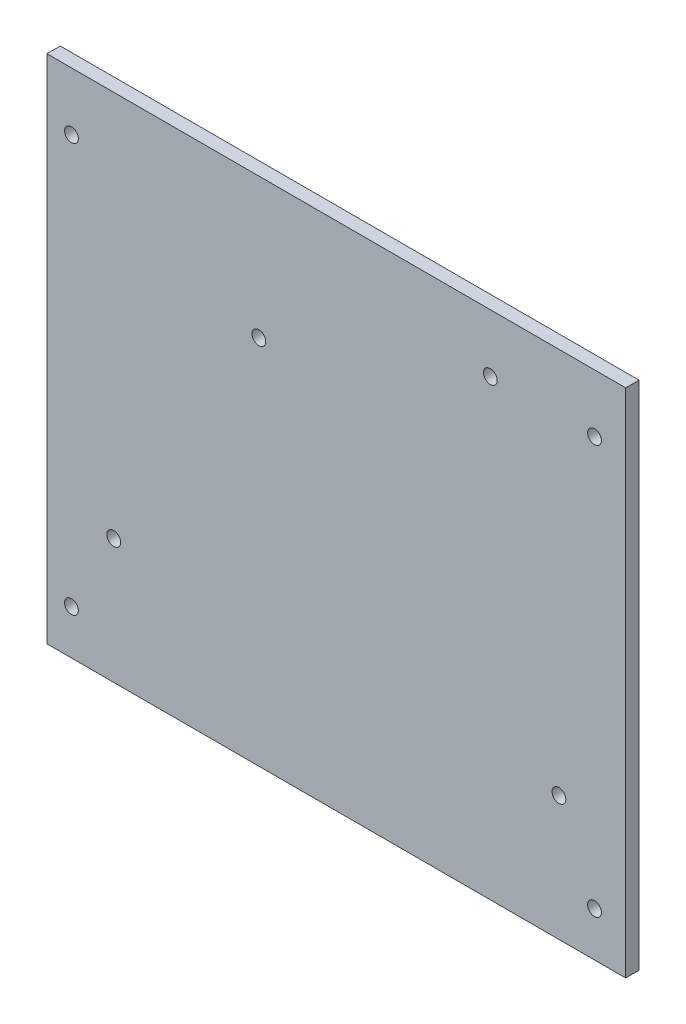
SolidWorks part; units mm, degrees
ref_plane "Front" through (0, 0, 0) normal (0, 0, 1) x (1, 0, 0)
ref_plane "Top" through (0, 0, 0) normal (0, 1, 0) x (1, 0, 0)
ref_plane "Right" through (0, 0, 0) normal (1, 0, 0) x (0, 0, -1)
sketch "Sketch1" plane through (0, 0, 0) normal (0, 0, 1) x (1, 0, 0)
  line L0 (65, 0) -> (0, 0) construction
  line L1 (-65, -57.4) -> (65, -57.4)
  line L2 (-65, -57.4) -> (-65, 57.4)
  line L3 (-65, 57.4) -> (65, 57.4)
  line L4 (65, -57.4) -> (65, 57.4)
  line L5 (-65, -57.4) -> (65, 57.4) construction
  line L6 (-65, 57.4) -> (65, -57.4) construction
  circle A0 centre (-59.5, 44.4) radius 1.55
  circle A1 centre (58, 44.4) radius 1.55
  circle A4 centre (58, -47.4) radius 1.55
  circle A5 centre (-59.5, -47.4) radius 1.55
  point P0 (0, 0)
  point P16 (0, 0)
  point P17 (0, 0)
  point P18 (0, 0)
  dimension "D3" = 3.1
  dimension "D4" = 3.1
  dimension "D5" = 13
  dimension "D6" = 5.5
  dimension "D7" = 7
  dimension "D8" = 3.1
  dimension "D9" = 3.1
  dimension "D10" = 10
  dimension "D1" = 114.8
  dimension "D2" = 130
extrude "Boss-Extrude1" add sketch "Sketch1" along normal blind 3
sketch "Sketch2" plane through (0, 0, 3) normal (0, 0, 1) x (1, 0, 0)
  line L1 (-44.5, -37.5) -> (44.5, -37.5)
  line L2 (-44.5, -37.5) -> (-44.5, 34.5)
  line L3 (-44.5, 34.5) -> (44.5, 34.5)
  line L4 (44.5, -37.5) -> (44.5, 34.5)
  line L5 (-44.5, -37.5) -> (44.5, 34.5) construction
  line L6 (-44.5, 34.5) -> (44.5, -37.5) construction
  point P0 (0, -1.5)
  point P5 (-11.1684, 6.8196)
  point P6 (0, 0)
  point P8 (45.7967, 26.409)
  point P9 (0, 0)
  point P10 (19.9433, 24.3731)
  point P11 (-24.5567, -11.6269)
  point P12 (0, 0)
  dimension "D1" = 72
  dimension "D2" = 89
  dimension "D3" = 1.5
extrude "Boss-Extrude2" [suppressed] add sketch "Sketch2" along normal blind 4
sketch "Sketch3" plane through (0, 0, 0) normal (0, 0, -1) x (-1, 0, 0)
  line L0 (65, -57.4) -> (-65, -57.4) construction
  circle A0 centre (-50, -29.4) radius 1.55
  circle A1 centre (50, -29.4) radius 1.55
  point P4 (0, 0)
  dimension "D1" = 3.1
  dimension "D2" = 3.1
  dimension "D4" = 100
  dimension "D3" = 28
  dimension "D5" = 50
extrude "Cut-Extrude1" cut sketch "Sketch3" against normal up to next
sketch "Sketch4" plane through (0, 0, 0) normal (0, 0, -1) x (-1, 0, 0)
  line L0 (-65, 57.4) -> (65, 57.4) construction
  line L1 (-65, -57.4) -> (-65, 57.4) construction
  line L2 (65, 57.4) -> (65, -57.4) construction
  circle A0 centre (-34.6, 44.4) radius 1.55
  circle A1 centre (17.4, 25.96) radius 1.55
  dimension "D1" = 3.1
  dimension "D2" = 3.1
  dimension "D3" = 13
  dimension "D4" = 30.4
  dimension "D5" = 47.6
  dimension "D6" = 31.44
extrude "Cut-Extrude2" cut sketch "Sketch4" against normal up to next
